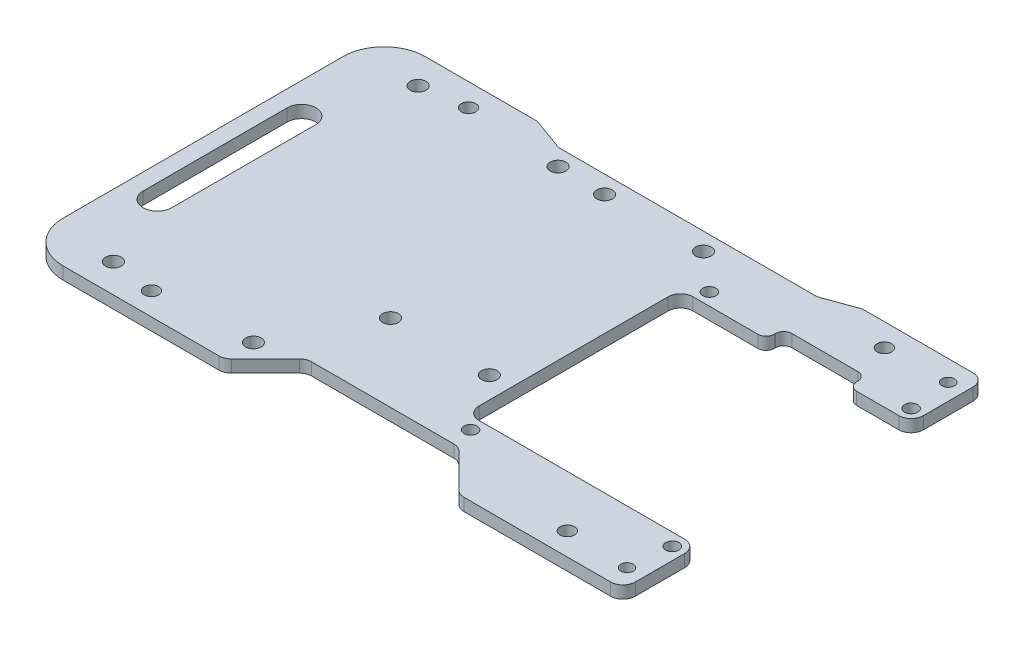
SolidWorks part; units mm, degrees
material "Perspex (TM) GS Acrylic Cast Sheet"
ref_plane "Front Plane" through (0, 0, 0) normal (0, 0, 1) x (1, 0, 0)
ref_plane "Top Plane" through (0, 0, 0) normal (0, 1, 0) x (1, 0, 0)
ref_plane "Right Plane" through (0, 0, 0) normal (1, 0, 0) x (0, 0, -1)
sketch "Sketch1" plane through (0, 0, 0) normal (0, 1, 0) x (1, 0, 0)
  line L0 (-45, -38.5) -> (56, -38.5) construction
  line L2 (-75, -44) -> (-75, -35)
  line L4 (75, -44) -> (75, -26)
  line L5 (-75, -44) -> (75, 44) construction
  line L6 (-75, 44) -> (75, -44) construction
  line L7 (56, 38.5) -> (56, -38.5) construction
  line L8 (-75, 35) -> (-71, 30)
  line L9 (-71, 30) -> (-71, -30)
  line L10 (-71, -30) -> (-75, -35)
  line L11 (75, 26) -> (59.7676, 26)
  line L12 (19, 26) -> (19, -26)
  line L13 (19, -26) -> (75, -26)
  line L14 (-75, 35) -> (-75, 44)
  line L15 (75, 26) -> (75, 44)
  line L19 (-63.5, 16.45) -> (-63.5, -18.55) construction
  line L20 (-60, 16.45) -> (-60, -18.55)
  line L21 (-67, 16.45) -> (-67, -18.55)
  line L28 (75, 44) -> (45.1626, 44)
  line L29 (75, -44) -> (35.1582, -44)
  line L30 (35.1582, -44) -> (25.1582, -34)
  line L31 (25.1582, -34) -> (-11.8418, -34)
  line L32 (-11.8418, -34) -> (-21.8418, -44)
  line L33 (-21.8418, -44) -> (-75, -44)
  line L35 (23, 29) -> (72, 29) construction
  line L36 (23, 29) -> (23, -29) construction
  line L37 (23, -29) -> (72, -29) construction
  line L38 (72, 29) -> (72, -29) construction
  line L39 (39.7676, 26) -> (39.7676, 30.2779)
  line L40 (39.7676, 30.2779) -> (59.7676, 30.2779)
  line L41 (59.7676, 30.2779) -> (59.7676, 26)
  line L43 (39.7676, 26) -> (19, 26)
  line L45 (13.7646, 36.7859) -> (-10.2354, 36.7859) construction
  line L46 (13.7646, 36.7859) -> (13.7646, -15.2141) construction
  line L47 (13.7646, -15.2141) -> (-10.2354, -15.2141) construction
  line L48 (-10.2354, 36.7859) -> (-10.2354, -15.2141) construction
  line L49 (-21.7465, 37) -> (-55.7465, 37) construction
  line L50 (-21.7465, 37) -> (-21.7465, -37) construction
  line L51 (-21.7465, -37) -> (-55.7465, -37) construction
  line L52 (-55.7465, 37) -> (-55.7465, -37) construction
  line L53 (-33.7721, 44) -> (-25.7216, 41.0699)
  line L54 (-25.7216, 41.0699) -> (37.1122, 41.0699)
  line L55 (37.1122, 41.0699) -> (45.1626, 44)
  line L56 (-33.7721, 44) -> (-75, 44)
  circle A56 centre (-45, 38.5) radius 1.75
  circle A57 centre (56, 38.5) radius 1.75
  circle A58 centre (56, -38.5) radius 1.75
  circle A59 centre (-45, -38.5) radius 1.75
  arc A62 (-60, 16.45) -> (-67, 16.45) centre (-63.5, 16.45) ccw
  arc A63 (-67, -18.55) -> (-60, -18.55) centre (-63.5, -18.55) ccw
  circle A65 centre (23, 29) radius 1.6
  circle A66 centre (72, 29) radius 1.6
  circle A67 centre (72, -29) radius 1.6
  circle A68 centre (23, -29) radius 1.6
  circle A69 centre (-55.7465, 37) radius 1.9
  circle A70 centre (-10.2354, 36.7859) radius 1.9
  circle A71 centre (13.7646, 36.7859) radius 1.9
  circle A72 centre (13.7646, -15.2141) radius 1.9
  circle A73 centre (-10.2354, -15.2141) radius 1.9
  circle A74 centre (-55.7465, -37) radius 1.9
  circle A75 centre (-21.7465, -37) radius 1.9
  circle A76 centre (-21.7465, 37) radius 1.9
  point P14 (0, 0)
  point P15 (56, 0)
  point P26 (-71, 0)
  point P27 (19, 0)
  point P31 (-63.5, -1.05)
  point P63 (-55.7465, 0)
  dimension "D2" = 3.5
  dimension "D11" = 225
  dimension "D20" = 42.95
  dimension "D22" = 3.8
  dimension "D32" = 3.2
  dimension "D1" = 88
  dimension "D3" = 77
  dimension "D4" = 101
  dimension "D5" = 30
  dimension "D6" = 4
  dimension "D9" = 56
  dimension "D10" = 52
  dimension "D7" = 9
  dimension "D8" = 5
  dimension "D12" = 7
  dimension "D13" = 4
  dimension "D14" = 35
  dimension "D15" = 150
  dimension "D16" = 225
  dimension "D17" = 200
  dimension "D18" = 37
  dimension "D19" = 200
  dimension "D21" = 5
  dimension "D23" = 49
  dimension "D24" = 58
  dimension "D25" = 3
  dimension "D26" = 3
  dimension "D27" = 20
  dimension "D28" = 34
  dimension "D29" = 74
  dimension "D30" = 24
  dimension "D31" = 52
extrude "Boss-Extrude1" add sketch "Sketch1" along normal blind 3
fillet "Fillet1" radius 3 16 edges at (75, 1.5, -26) (75, 1.5, 26) (19, 1.5, 26) (75, 1.5, -44) (-75, 1.5, 44) (-21.8418, 1.5, 44) (-11.8418, 1.5, 34) (25.1582, 1.5, 34) (35.1582, 1.5, 44) (75, 1.5, 44) (19, 1.5, -26) (-25.7216, 1.5, -41.0699) (-33.7721, 1.5, -44) (37.1122, 1.5, -41.0699) (45.1626, 1.5, -44) (-75, 1.5, -44)
fillet "Fillet2" radius 7 2 edges at (-71, 1.5, 30) (-71, 1.5, -30)
fillet "Fillet3" radius 2 4 edges at (39.7676, 1.5, -26) (39.7676, 1.5, -30.2779) (59.7676, 1.5, -26) (59.7676, 1.5, -30.2779)
sketch "Sketch2" plane through (0, 3, 0) normal (0, 1, 0) x (1, 0, 0)
  line L0 (75, 29) -> (75, 41) construction
  line L1 (72, 44) -> (45.6916, 44) construction
  line L2 (36.4008, -44) -> (72, -44) construction
  circle A0 centre (71, 39) radius 1.5
  circle A1 centre (71, -39) radius 1.5
  dimension "D2" = 3
  dimension "D1" = 4
  dimension "D3" = 5
  dimension "D4" = 5
extrude "Cut-Extrude1" cut sketch "Sketch2" against normal blind 10
sketch "Sketch3" plane through (0, 3, 0) normal (0, 1, 0) x (1, 0, 0)
  line L0 (-71, -47.7578) -> (-71, 47.7578)
  line L2 (-71, 47.7578) -> (-93.305, 47.7578)
  line L3 (-93.305, 47.7578) -> (-93.305, -47.7578)
  line L4 (-93.305, -47.7578) -> (-71, -47.7578)
  point P3 (-71, 0)
extrude "Cut-Extrude2" cut sketch "Sketch3" against normal blind 10
fillet "Fillet4" radius 10 2 edges at (-71, 1.5, 44) (-71, 1.5, -44)
